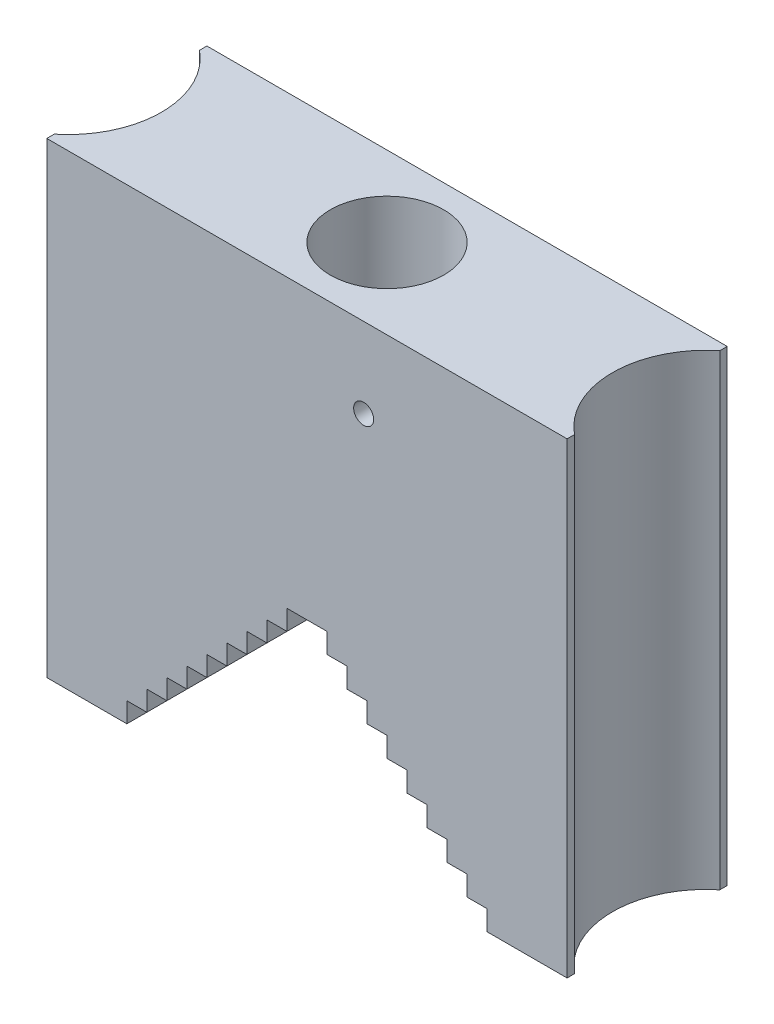
SolidWorks part; units mm, degrees
ref_plane "Płaszczyzna przednia" through (0, 0, 0) normal (0, 0, 1) x (1, 0, 0)
ref_plane "Płaszczyzna górna" through (0, 0, 0) normal (0, 1, 0) x (1, 0, 0)
ref_plane "Płaszczyzna prawa" through (0, 0, 0) normal (1, 0, 0) x (0, 0, -1)
sketch "Sketch1" plane through (0, 0, 0) normal (0, 0, 1) x (1, 0, 0)
  line L1 (-39, -35) -> (39, -35)
  line L2 (-39, -35) -> (-39, 35)
  line L3 (-39, 35) -> (39, 35)
  line L4 (39, -35) -> (39, 35)
  line L5 (-39, -35) -> (39, 35) construction
  line L6 (-39, 35) -> (39, -35) construction
  point P0 (0, 0)
  dimension "D1" = 78
  dimension "D2" = 70
extrude "Boss-Extrude1" add sketch "Sketch1" along normal mid plane 24
hole_wizard "Ø17.0 (17) Diameter Hole1" positions "Sketch3" profile "Sketch4" hole size "Ø17.0" standard "ISO"
sketch "Sketch3" plane through (0, 35, 0) normal (0, 1, 0) x (1, 0, 0)
  point P0 (0, 0)
sketch "Sketch4" plane through (0, 35, 0) normal (1, 0, 0) x (0, 0, 1)
  line L0 (0, 0) -> (0, 30.1073)
  line L1 (0, 30.1073) -> (8.5, 25)
  line L2 (8.5, 25) -> (8.5, 0)
  line L5 (8.5, 0) -> (0, 0)
  line L10 (0, 30.1073) -> (-8.5, 25) construction
  line L11 (0, -6.35) -> (0, 107.95) construction
  dimension "Hole Dia." = 17
  dimension "Hole Depth" = 25
  dimension "Drill Angle" = 118
hole_wizard "Ø3.0 (3) Diameter Hole1" positions "Sketch6" profile "Sketch7" hole size "Ø3.0" standard "ISO" end condition through all
sketch "Sketch6" plane through (0, 0, 12) normal (0, 0, 1) x (1, 0, 0)
  line L0 (39, 35) -> (-39, 35) construction
  point P0 (8.5, 23)
  dimension "D1" = 8.5
  dimension "D2" = 12
sketch "Sketch7" plane through (8.5, 23, 12) normal (1, 0, 0) x (0, -1, 0)
  line L0 (0, 0) -> (0, 24)
  line L1 (0, 24) -> (1.5, 24)
  line L2 (1.5, 24) -> (1.5, 0)
  line L5 (1.5, 0) -> (0, 0)
  line L11 (0, -6.35) -> (0, 107.95) construction
  dimension "Thru Hole Dia." = 3
  dimension "Thru Hole Depth" = 24
sketch "Sketch8" plane through (0, 35, 0) normal (0, 1, 0) x (1, 0, 0)
  line L0 (0, 0) -> (0, 25.0245) construction
  line L1 (0, 0) -> (-47.8, 0) construction
  circle A0 centre (-47.8, 0) radius 14
  circle A1 centre (47.8, 0) radius 14
  dimension "D2" = 28
  dimension "D1" = 47.8
extrude "Cut-Extrude1" cut sketch "Sketch8" against normal up to next
sketch "Sketch9" plane through (0, 0, 12) normal (0, 0, 1) x (1, 0, 0)
  line L0 (-39, -35) -> (39, -35) construction
  line L1 (-27, -35) -> (27, -35) construction
  line L2 (0, -35) -> (0, -8) construction
  line L3 (-27, -8) -> (27, -8) construction
  line L4 (27, -35) -> (27, -8) construction
  line L5 (0, -35) -> (27, -8) construction
  line L6 (0, -8) -> (27, -35) construction
  line L7 (27, -35) -> (27, -32)
  line L8 (27, -32) -> (24, -32)
  line L9 (24, -32) -> (24, -29)
  line L10 (24, -29) -> (21, -29)
  line L11 (21, -29) -> (21, -26)
  line L12 (21, -26) -> (18, -26)
  line L13 (18, -26) -> (18, -23)
  line L14 (18, -23) -> (15, -23)
  line L15 (15, -23) -> (15, -20)
  line L16 (15, -20) -> (12, -20)
  line L17 (12, -20) -> (12, -17)
  line L18 (12, -17) -> (9, -17)
  line L19 (9, -17) -> (9, -14)
  line L20 (9, -14) -> (6, -14)
  line L21 (6, -14) -> (6, -11)
  line L22 (6, -11) -> (3, -11)
  line L23 (3, -11) -> (3, -8)
  line L24 (3, -8) -> (0, -8)
  line L25 (0, -8) -> (-27, -35) construction
  line L26 (0, -35) -> (-27, -8) construction
  line L27 (-27, -35) -> (-27, -8) construction
  line L28 (-3, -8) -> (0, -8)
  line L29 (-3, -11) -> (-3, -8)
  line L30 (-6, -11) -> (-3, -11)
  line L31 (-6, -14) -> (-6, -11)
  line L32 (-9, -14) -> (-6, -14)
  line L33 (-9, -17) -> (-9, -14)
  line L34 (-12, -17) -> (-9, -17)
  line L35 (-12, -20) -> (-12, -17)
  line L36 (-15, -20) -> (-12, -20)
  line L37 (-15, -23) -> (-15, -20)
  line L38 (-18, -23) -> (-15, -23)
  line L39 (-18, -26) -> (-18, -23)
  line L40 (-21, -26) -> (-18, -26)
  line L41 (-21, -29) -> (-21, -26)
  line L42 (-24, -29) -> (-21, -29)
  line L43 (-24, -32) -> (-24, -29)
  line L44 (-27, -32) -> (-24, -32)
  line L45 (-27, -35) -> (-27, -32)
  line L46 (-27, -35) -> (27, -35)
  point P4 (13.5, -21.5)
  point P45 (-13.5, -21.5)
  line M28 (-39, -35) -> (39, -35)
  dimension "D1" = 27
  dimension "D2" = 27
  dimension "D3" = 3
  dimension "D4" = 3
extrude "Cut-Extrude2" cut sketch "Sketch9" against normal through all contours L45 L7 L8 L9 L10 L11 L12 L13 L14 L15 L16 L17 L18 L19 L20 L21 L22 L23 L24 L28 L29 L30 L31 L32 L33 L34 L35 L36 L37 L38 L39 L40 L41 L42 L43 L44 M28
